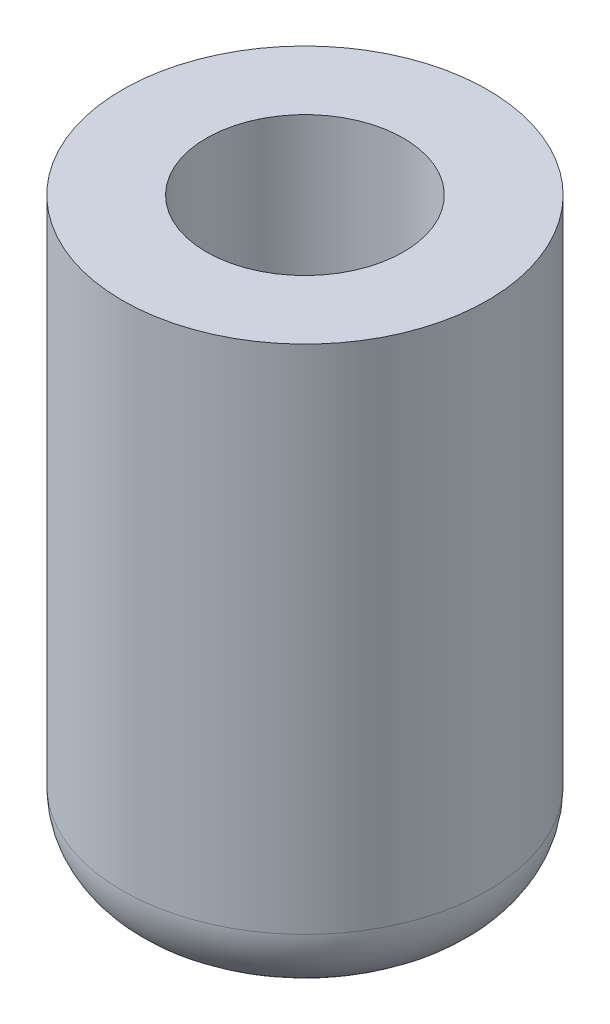
SolidWorks part; units mm, degrees
ref_plane "Front Plane" through (0, 0, 0) normal (0, 0, 1) x (1, 0, 0)
ref_plane "Top Plane" through (0, 0, 0) normal (0, 1, 0) x (1, 0, 0)
ref_plane "Right Plane" through (0, 0, 0) normal (1, 0, 0) x (0, 0, -1)
sketch "Sketch1" plane through (0, 0, 0) normal (0, 1, 0) x (1, 0, 0)
  circle A1 centre (0, 0) radius 6.35
  dimension "D2" = 12.7
extrude "Boss-Extrude1" add sketch "Sketch1" along normal blind 20.32
sketch "Sketch2" plane through (0, 20.32, 0) normal (0, 1, 0) x (1, 0, 0)
  circle A0 centre (0, 0) radius 3.429
  dimension "D1" = 6.858
extrude "Cut-Extrude1" cut sketch "Sketch2" against normal blind 17.78 contours A0
fillet "Fillet1" radius 2.54 1 edges at (0, 0, 6.35)
